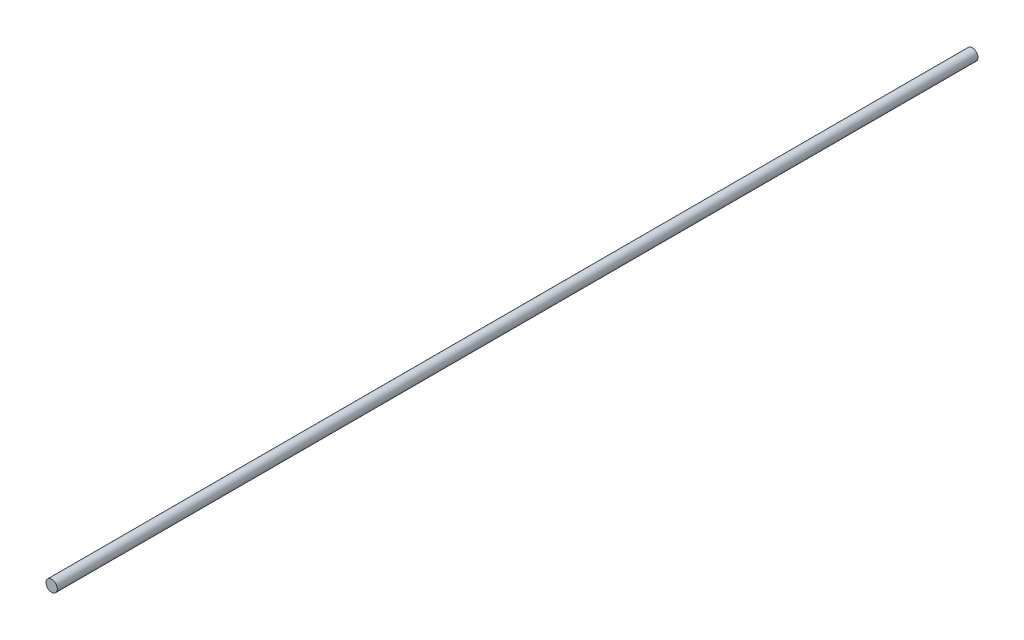
SolidWorks part; units mm, degrees
ref_plane "Front" through (0, 0, 0) normal (0, 0, 1) x (1, 0, 0)
ref_plane "Top" through (0, 0, 0) normal (0, 1, 0) x (1, 0, 0)
ref_plane "Right" through (0, 0, 0) normal (1, 0, 0) x (0, 0, -1)
sketch "Sketch1" plane through (0, 0, 0) normal (0, 0, 1) x (1, 0, 0)
  circle A0 centre (0, 0) radius 4
  dimension "D1" = 8
extrude "Boss-Extrude1" add sketch "Sketch1" along normal mid plane 650
